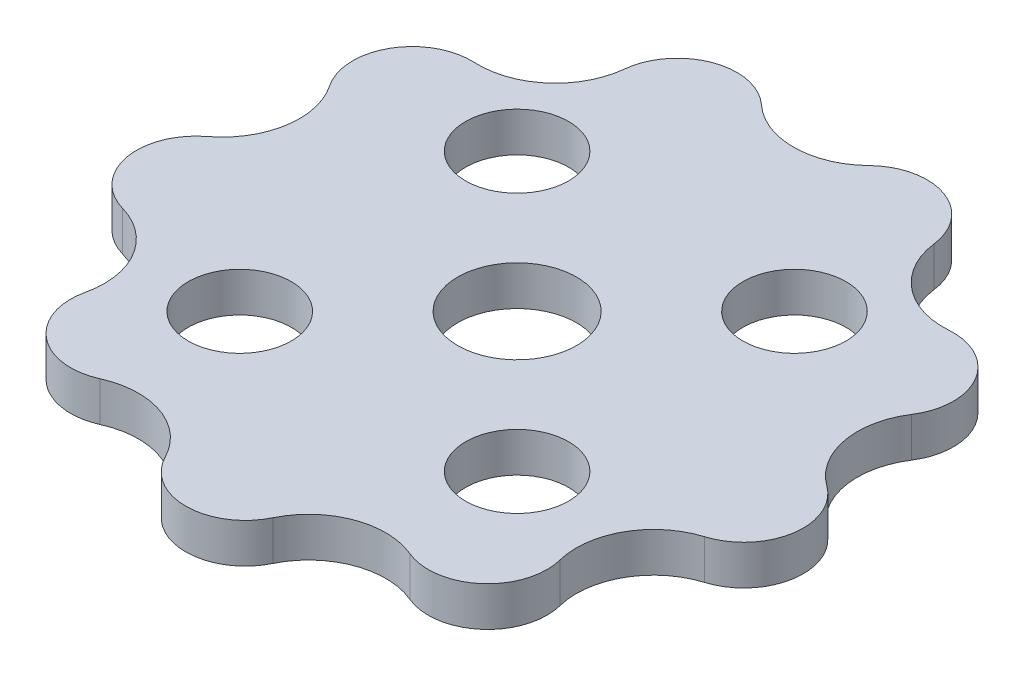
SolidWorks part; units mm, degrees
ref_plane "Front Plane" through (0, 0, 0) normal (0, 0, 1) x (1, 0, 0)
ref_plane "Top Plane" through (0, 0, 0) normal (0, 1, 0) x (1, 0, 0)
ref_plane "Right Plane" through (0, 0, 0) normal (1, 0, 0) x (0, 0, -1)
sketch "Sketch1" plane through (0, 0, 0) normal (0, 1, 0) x (1, 0, 0)
  line L0 (0, 0) -> (22.9976, 65.5) construction
  arc A0 (-14.2871, 75.9583) -> (12.5511, 76.2643) centre (-1.0293, 90.258) ccw
  arc A1 (12.5511, 76.2643) -> (37.8805, 67.371) centre (22.9976, 65.5) cw
  arc A3 (37.8805, 67.371) -> (58.6365, 50.3542) centre (57.2282, 69.8032) ccw
  arc A4 (58.6365, 50.3542) -> (72.3234, 27.2601) centre (59.7198, 35.3933) cw
  arc A5 (72.3234, 27.2601) -> (77.2852, 0.8827) centre (88.708, 16.6868) ccw
  arc A6 (77.2852, 0.8827) -> (72.9253, -25.6061) centre (68.4984, -11.2743) cw
  arc A7 (72.9253, -25.6061) -> (59.7713, -49.0018) centre (78.6803, -44.2376) ccw
  arc A8 (59.7713, -49.0018) -> (39.4047, -66.4909) centre (45.2259, -52.6665) cw
  arc A9 (39.4047, -66.4909) -> (14.2897, -75.9578) centre (31.8373, -84.4627) ccw
  arc A10 (14.2897, -75.9578) -> (-12.5538, -76.2639) centre (0.7916, -69.4155) cw
  arc A11 (-12.5538, -76.2639) -> (-37.8781, -67.3723) centre (-29.9028, -85.1668) ccw
  arc A12 (-37.8781, -67.3723) -> (-58.6382, -50.3521) centre (-44.013, -53.6842) cw
  arc A13 (-58.6382, -50.3521) -> (-72.3224, -27.2626) centre (-77.651, -46.0204) ccw
  arc A14 (-72.3224, -27.2626) -> (-77.2852, -0.88) centre (-68.2235, -12.8335) cw
  arc A15 (-77.2852, -0.88) -> (-72.9262, 25.6036) centre (-89.0655, 14.6594) ccw
  arc A16 (-72.9262, 25.6036) -> (-59.7696, 49.0038) centre (-60.5114, 34.0222) cw
  arc A17 (-59.7696, 49.0038) -> (-39.407, 66.4896) centre (-58.8052, 68.48) ccw
  arc A18 (-39.407, 66.4896) -> (-14.2871, 75.9583) centre (-24.4854, 64.9585) cw
  point P51 (0, 0)
  dimension "D1" = 9
  dimension "D2" = 65.5
  dimension "D3" = 15
  dimension "D4" = 19.5
extrude "Boss-Extrude1" add sketch "Sketch1" along normal blind 10
sketch "Sketch2" plane through (0, 10, 0) normal (0, 1, 0) x (-1, 0, 0)
  line L0 (0, 0) -> (0, -109.7308) construction
  line L1 (0, 0) -> (-35, 35) construction
  circle A0 centre (-35, 35) radius 13
  arc A1 (14.2871, -75.9583) -> (-12.5511, -76.2643) centre (1.0293, -90.258) ccw construction
  circle A2 centre (35, 35) radius 13
  circle A3 centre (35, -35) radius 13
  circle A4 centre (-35, -35) radius 13
  point P16 (0, 0)
  dimension "D1" = 26
  dimension "D2" = 35
  dimension "D3" = 45
  dimension "D4" = 4
extrude "Cut-Extrude1" cut sketch "Sketch2" against normal blind 10 contours A4
sketch "Sketch3" plane through (0, 10, 0) normal (0, 1, 0) x (1, 0, 0)
  circle A0 centre (0, 0) radius 15
  dimension "D1" = 30
extrude "Cut-Extrude2" cut sketch "Sketch3" against normal blind 10
